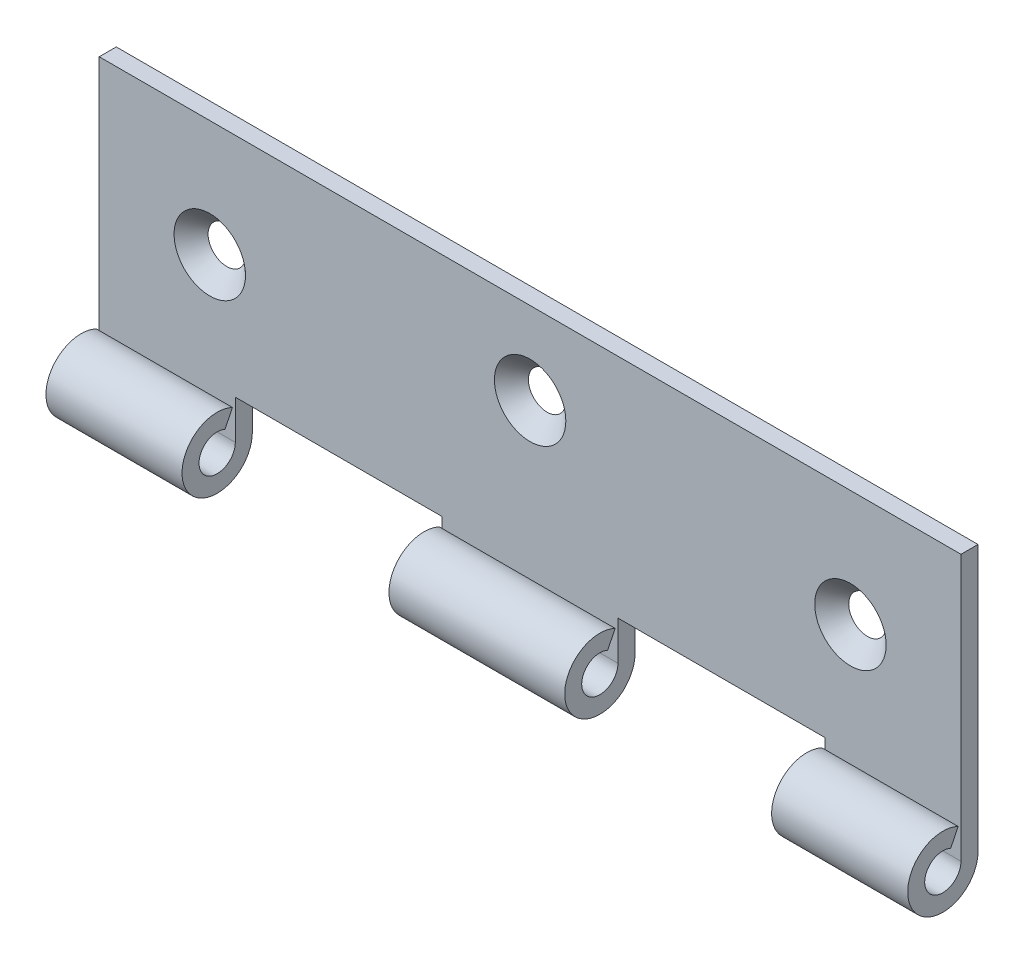
SolidWorks part; units mm, degrees
material "Alloy Steel"
ref_plane "Front" through (0, 0, 0) normal (0, 0, 1) x (1, 0, 0)
ref_plane "Top" through (0, 0, 0) normal (0, 1, 0) x (1, 0, 0)
ref_plane "Right" through (0, 0, 0) normal (1, 0, 0) x (0, 0, -1)
sketch "Sketch1" plane through (0, 0, 0) normal (0, 0, 1) x (1, 0, 0)
  line L0 (-38, 10) -> (38, -10) construction
  line L1 (-38, -10) -> (38, -10)
  line L2 (-38, -10) -> (-38, 10)
  line L3 (-38, 10) -> (38, 10)
  line L4 (38, -10) -> (38, 10)
  dimension "D1" = 20
  dimension "D2" = 76
extrude "Extrude1" add sketch "Sketch1" along normal blind 1.5
sketch "Sketch2" plane through (0, -10, 0) normal (0, -1, 0) x (1, 0, 0)
  line L0 (-38, 0) -> (38, 0) construction
  line L1 (-38, 1.5) -> (-26, 1.5)
  line L2 (-38, 1.5) -> (-38, 0)
  line L3 (-38, 0) -> (-26, 0)
  line L4 (-26, 1.5) -> (-26, 0)
  dimension "D1" = 12
sketch "Sketch3" plane through (0, -10, 0) normal (0, -1, 0) x (1, 0, 0)
  line L0 (-38, 1.5) -> (38, 1.5) construction
  line L1 (-7.75, 1.5) -> (7.75, 1.5)
  line L2 (-7.75, 1.5) -> (-7.75, 0)
  line L3 (-7.75, 0) -> (7.75, 0)
  line L4 (7.75, 1.5) -> (7.75, 0)
  line L5 (-38, 0) -> (38, 0) construction
  line L6 (7.75, 1.5) -> (-7.75, 0) construction
  dimension "D1" = 15.5
sketch "Sketch4" plane through (0, -10, 0) normal (0, -1, 0) x (1, 0, 0)
  line L0 (-38, 1.5) -> (38, 1.5) construction
  line L1 (26, 1.5) -> (38, 1.5)
  line L2 (26, 1.5) -> (26, 0)
  line L3 (26, 0) -> (38, 0)
  line L4 (38, 1.5) -> (38, 0)
  line L5 (-38, 0) -> (38, 0) construction
  line L6 (38, 1.5) -> (38, 0) construction
  dimension "D1" = 12
ref_plane "Plane1" through (-32, 0, 0) normal (-1, 0, 0) x (0, 0, 1)
ref_plane "Plane2" through (32, 0, 0) normal (1, 0, 0) x (0, 0, -1)
ref_plane "Plane3" through (0, 0, 0) normal (1, 0, 0) x (0, 0, -1)
sketch "Sketch5" plane through (0, 0, 0) normal (1, 0, 0) x (0, 0, -1)
  line L0 (-0.75, -10) -> (-0.75, -13.45)
  line L1 (-1.5, -10) -> (0, -10) construction
  arc A0 (-0.75, -13.45) -> (-2.0825, -11.3317) centre (-3.1, -13.45) cw
  dimension "D1" = 2.35
  dimension "D2" = 5.8
sweep "Sweep1" add profiles "Sketch3" path "Sketch5"
sketch "Sketch6" plane through (-32, 0, 0) normal (1, 0, 0) x (0, 0, -1)
  line L0 (-0.75, -10) -> (-0.75, -13.45)
  arc A0 (-0.75, -13.45) -> (-2.0825, -11.3317) centre (-3.1, -13.45) cw
sketch "Sketch7" plane through (32, 0, 0) normal (1, 0, 0) x (0, 0, -1)
  line L0 (-0.75, -10) -> (-0.75, -13.45)
  arc A0 (-0.75, -13.45) -> (-2.0825, -11.3317) centre (-3.1, -13.45) cw
sweep "Sweep2" add profiles "Sketch4" path "Sketch7"
sweep "Sweep3" add profiles "Sketch2" path "Sketch6"
sketch "Sketch8" plane through (0, 0, 1.5) normal (0, 0, 1) x (1, 0, 0)
  line L0 (38, 10) -> (-38, 10) construction
  line L1 (-38, 10) -> (-38, -13.45) construction
  line L2 (38, -13.45) -> (38, 10) construction
  point P0 (-28.25, -0.25)
  point P1 (0, 2.75)
  point P2 (28.25, -0.25)
  dimension "D1" = 10.25
  dimension "D2" = 9.75
  dimension "D3" = 9.75
  dimension "D4" = 7.25
hole_wizard "CSK for M3 Countersunk Flat Head Screw1" positions "3DSketch1" profile "Sketch9" countersink size "M3" standard "ISO" end condition through all
sketch3d "3DSketch1"
  point P0 (28.25, -0.25, 1.5)
  point P3 (0, 2.75, 1.5)
  point P6 (-28.25, -0.25, 1.5)
sketch "Sketch9" plane through (28.25, -0.25, 1.5) normal (1, 0, 0) x (0, -1, 0)
  line L0 (0, 0) -> (0, 1.5)
  line L1 (0, 1.5) -> (1.6, 1.5)
  line L2 (1.6, 1.5) -> (1.6, 1.55)
  line L3 (1.6, 1.55) -> (3.15, 0)
  line L5 (3.15, 0) -> (0, 0)
  line L6 (-1.6, 1.55) -> (-3.15, 0) construction
  line L11 (0, -6.35) -> (0, 107.95) construction
  dimension "Thru Hole Dia." = 3.2
  dimension "Thru Hole Depth" = 1.5
  dimension "Near C'Sink Dia." = 6.3
  dimension "Near C'Sink Angle" = 90
sketch "Sketch10" plane through (0, -10, 0) normal (0, -1, 0) x (1, 0, 0)
  line L0 (-38, 1.5) -> (38, 1.5) construction
  line L1 (-26.9245, 1.5) -> (-14.2361, 1.5)
  line L2 (-26.9245, 1.5) -> (-26.9245, 0)
  line L3 (-26.9245, 0) -> (-14.2361, 0)
  line L4 (-14.2361, 1.5) -> (-14.2361, 0)
  line L5 (-38, 0) -> (38, 0) construction
  line L6 (-26.9245, 1.5) -> (-14.2361, 0) construction
  line L7 (-38, 1.5) -> (-38, 0) construction
  dimension "D1" = 11.0755
  dimension "D2" = 12.6884
sketch "Sketch11" plane through (0, -10, 0) normal (0, -1, 0) x (1, 0, 0)
  line L0 (-38, 1.5) -> (38, 1.5) construction
  line L1 (9.7174, 1.5) -> (26.2, 1.5)
  line L2 (9.7174, 1.5) -> (9.7174, 0)
  line L3 (9.7174, 0) -> (26.2, 0)
  line L4 (26.2, 1.5) -> (26.2, 0)
  line L5 (-38, 0) -> (38, 0) construction
  line L6 (38, 1.5) -> (38, 0) construction
  line L7 (9.7174, 1.5) -> (26.2, 0) construction
  dimension "D1" = 11.8
  dimension "D2" = 16.4826
ref_plane "Plane4" [suppressed] through (-17.2, 0, 0) normal (-1, 0, 0) x (0, 0, 1)
ref_plane "Plane5" [suppressed] through (17.2, 0, 0) normal (1, 0, 0) x (0, 0, -1)
sketch "Sketch12" [suppressed] plane through (-17.2, 0, 0) normal (-1, 0, 0) x (0, 0, 1)
  line L0 (0.75, -10) -> (0.75, -13.45)
  line L1 (1.5, -10) -> (0, -10) construction
  arc A0 (0.75, -13.45) -> (2.2309, -11.2666) centre (3.1, -13.45) ccw
  dimension "D2" = 2.35
  dimension "D1" = 3.5902
sketch "Sketch13" [suppressed] plane through (17.2, 0, 0) normal (-1, 0, 0) x (0, 0, 1)
  line L0 (0.75, -10) -> (0.75, -13.45)
  arc A0 (0.75, -13.45) -> (2.2309, -11.2666) centre (3.1, -13.45) ccw
sweep "Sweep4" [suppressed] add profiles "Sketch10" path "Sketch12"
sweep "Sweep5" [suppressed] add profiles "Sketch11" path "Sketch13"
